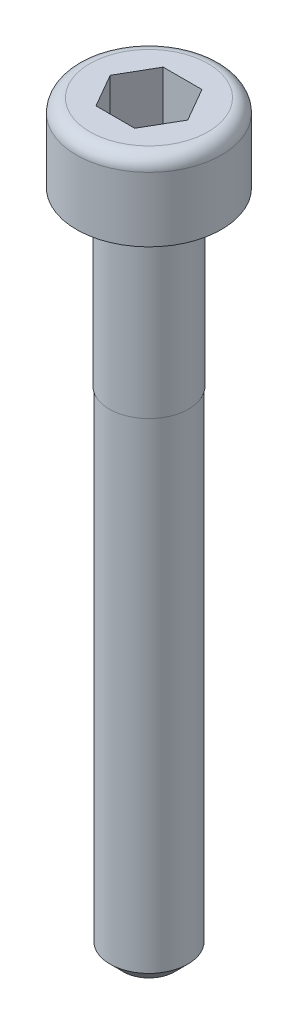
SolidWorks part; units mm, degrees
material "1023 Tôle d'acier au carbone (SS)"
ref_plane "Plan de face" through (0, 0, 0) normal (0, 0, 1) x (1, 0, 0)
ref_plane "Plan de dessus" through (0, 0, 0) normal (0, 1, 0) x (1, 0, 0)
ref_plane "Plan de droite" through (0, 0, 0) normal (1, 0, 0) x (0, 0, -1)
sketch "Esquisse1" plane through (0, 0, 0) normal (0, 0, 1) x (1, 0, 0)
  line L0 (0, 15.8257) -> (0, -15.8257) construction
  line L1 (0, 2.9) -> (-2.2, 2.9)
  line L2 (-2.7, 2.4) -> (-2.7, 0)
  line L3 (-2.7, 0) -> (-1.475, 0)
  line L4 (-1.45, -6.4) -> (-1.45, -24.3)
  line L5 (-1.45, -24.3) -> (-0.95, -24.8)
  line L6 (-0.95, -24.8) -> (0, -24.8)
  line L7 (0, 2.9) -> (0, -24.8)
  line L8 (-1.475, 0) -> (-1.475, -6.4)
  line L9 (-1.475, -6.4) -> (-1.45, -6.4)
  arc A0 (-2.2, 2.9) -> (-2.7, 2.4) centre (-2.2, 2.4) ccw
  point P11 (-1.45, -24.8)
  dimension "D5" = 0.5
  dimension "D1" = 5.4
  dimension "D2" = 2.95
  dimension "D3" = 24.8
  dimension "D4" = 2.9
  dimension "D8" = 0.5
  dimension "D6" = 2.9
  dimension "D7" = 6.4
revolve "Révolution1" add sketch "Esquisse1" angle 360 about L0
cosmetic thread "Représentation de filetage1" parameters "D2"=2.3
sketch "Esquisse2" plane through (0, 2.9, 0) normal (0, 1, 0) x (-1, 0, 0)
  line L1 (-1.4434, 0) -> (-0.7217, -1.25)
  line L2 (-0.7217, -1.25) -> (0.7217, -1.25)
  line L3 (0.7217, -1.25) -> (1.4434, 0)
  line L4 (1.4434, 0) -> (0.7217, 1.25)
  line L5 (0.7217, 1.25) -> (-0.7217, 1.25)
  line L6 (-0.7217, 1.25) -> (-1.4434, 0)
  circle A0 centre (0, 0) radius 1.25 construction
  dimension "D1" = 2.5
extrude "Enlèv. mat.-Extru.1" cut sketch "Esquisse2" against normal blind 2
